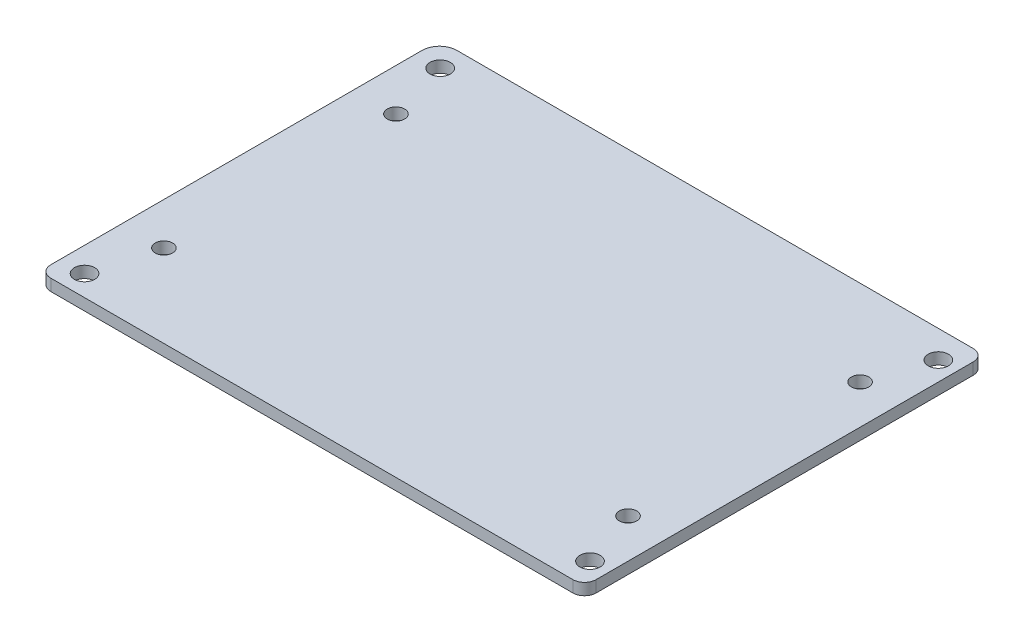
SolidWorks part; units mm, degrees
material "A-玻璃纤维"
ref_plane "前视基准面" through (0, 0, 0) normal (0, 0, 1) x (1, 0, 0)
ref_plane "上视基准面" through (0, 0, 0) normal (0, 1, 0) x (1, 0, 0)
ref_plane "右视基准面" through (0, 0, 0) normal (1, 0, 0) x (0, 0, -1)
sketch "草图1" plane through (0, 0, 0) normal (0, 1, 0) x (1, 0, 0)
  line L0 (-33.2164, 0) -> (30.5174, 0) construction
  line L1 (-44.2482, 34.7487) -> (44.7518, 34.7487)
  line L2 (-47.2482, 31.7487) -> (-47.2482, -32.2513)
  line L3 (-45.2482, -34.2513) -> (44.7518, -34.2513)
  line L4 (46.7518, 32.7487) -> (46.7518, -32.2513)
  line L5 (-0.2482, -34.2513) -> (0.2518, 34.7487) construction
  arc A0 (44.7518, 34.7487) -> (46.7518, 32.7487) centre (44.7518, 32.7487) cw
  arc A1 (-47.2482, -32.2513) -> (-45.2482, -34.2513) centre (-45.2482, -32.2513) ccw
  arc A2 (-44.2482, 34.7487) -> (-47.2482, 31.7487) centre (-44.2482, 31.7487) ccw
  arc A3 (44.7518, -34.2513) -> (46.7518, -32.2513) centre (44.7518, -32.2513) ccw
  circle A4 centre (-43.029, 30.65) radius 1.75
  circle A5 centre (43.4687, 30.0232) radius 1.75
  circle A7 centre (43.4687, -30.0232) radius 1.75
  circle A8 centre (-43.029, -30.65) radius 1.75
  point P0 (0, 0)
  point P6 (46.7518, 34.7487)
  point P12 (-47.2482, -34.2513)
  point P15 (-47.2482, 34.7487)
  dimension "D3" = 2
  dimension "D4" = 2
  dimension "D5" = 3
  dimension "D6" = 2
  dimension "D7" = 3.5
  dimension "D8" = 90
  dimension "D9" = 64.8
  dimension "D1" = 69
  dimension "D2" = 94
extrude "凸台-拉伸1" add sketch "草图1" along normal blind 2
sketch "草图3" plane through (0, 2, 0) normal (0, 1, 0) x (1, 0, 0)
  line L1 (-40, 20) -> (40, 20) construction
  line L2 (-40, 20) -> (-40, -20) construction
  line L3 (-40, -20) -> (40, -20) construction
  line L4 (40, 20) -> (40, -20) construction
  line L5 (0, -20) -> (0, 20) construction
  line L6 (-40, 0) -> (40, 0) construction
  circle A0 centre (-40, -20) radius 1.5
  circle A1 centre (40, -20) radius 1.5
  circle A2 centre (40, 20) radius 1.5
  circle A3 centre (-40, 20) radius 1.5
  point P0 (0, 0)
  dimension "D3" = 3
  dimension "D1" = 40
  dimension "D2" = 80
  dimension "D4" = 2
  dimension "D5" = 2
extrude "切除-拉伸1" cut sketch "草图3" against normal blind 10
